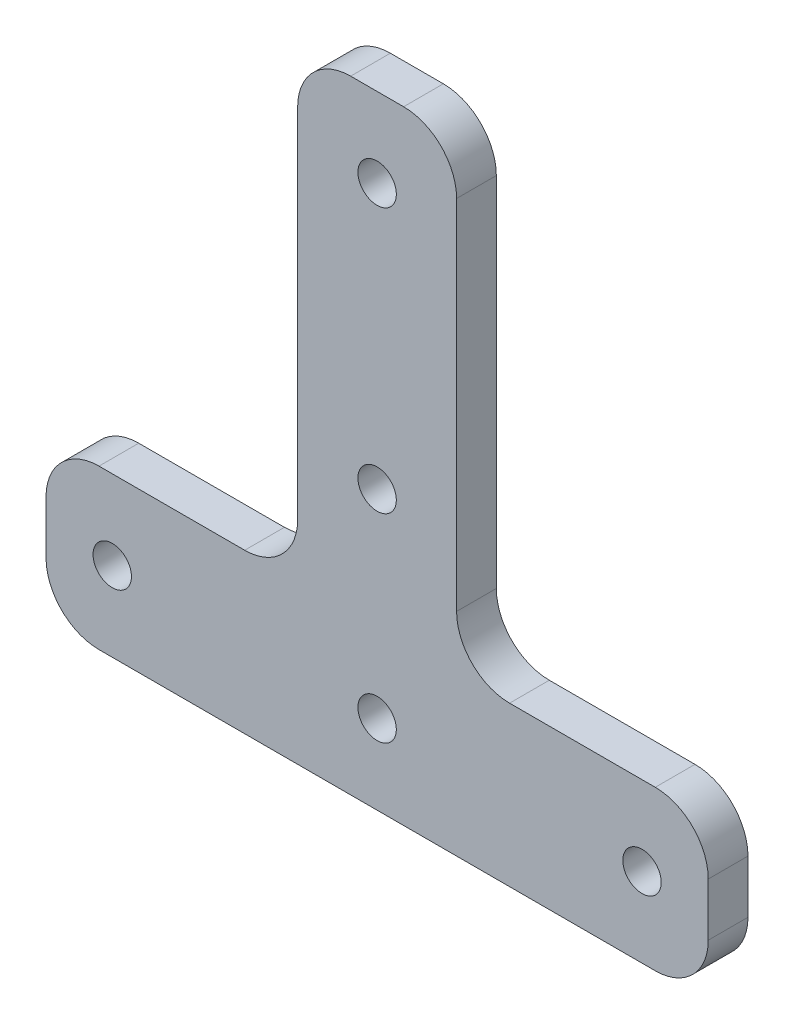
SolidWorks part; units mm, degrees
material "Thornel Mat VMA"
ref_plane "前视基准面" through (0, 0, 0) normal (0, 0, 1) x (1, 0, 0)
ref_plane "上视基准面" through (0, 0, 0) normal (0, 1, 0) x (1, 0, 0)
ref_plane "右视基准面" through (0, 0, 0) normal (1, 0, 0) x (0, 0, -1)
sketch "草图1" plane through (0, 0, 0) normal (0, 0, 1) x (1, 0, 0)
  line L0 (20, 0) -> (-20, 0) construction
  line L1 (0, 0) -> (0, 35) construction
  line L2 (-6, 6) -> (-25, 6)
  line L3 (-25, 6) -> (-25, -6)
  line L4 (-25, -6) -> (25, -6)
  line L5 (25, -6) -> (25, 6)
  line L6 (25, 6) -> (6, 6)
  line L7 (6, 6) -> (6, 41)
  line L8 (6, 41) -> (-6, 41)
  line L9 (-6, 41) -> (-6, 6)
  circle A0 centre (0, 35) radius 1.45
  circle A1 centre (0, 0) radius 1.45
  circle A2 centre (-20, 0) radius 1.45
  circle A3 centre (20, 0) radius 1.45
  circle A4 centre (0, 15) radius 1.45
  point P4 (0, 0)
  dimension "D1" = 20
  dimension "D2" = 15
  dimension "D3" = 20
  dimension "D4" = 2.9
  dimension "D5" = 6
  dimension "D8" = 6
  dimension "D9" = 5
  dimension "D10" = 6
  dimension "D11" = 5
  dimension "D6" = 6
  dimension "D7" = 6
extrude "凸台-拉伸1" add sketch "草图1" along normal blind 3
fillet "圆角1" radius 4 8 edges at (-6, 41, 1.5) (6, 41, 1.5) (25, 6, 1.5) (25, -6, 1.5) (-25, -6, 1.5) (-25, 6, 1.5) (-6, 6, 1.5) (6, 6, 1.5)
